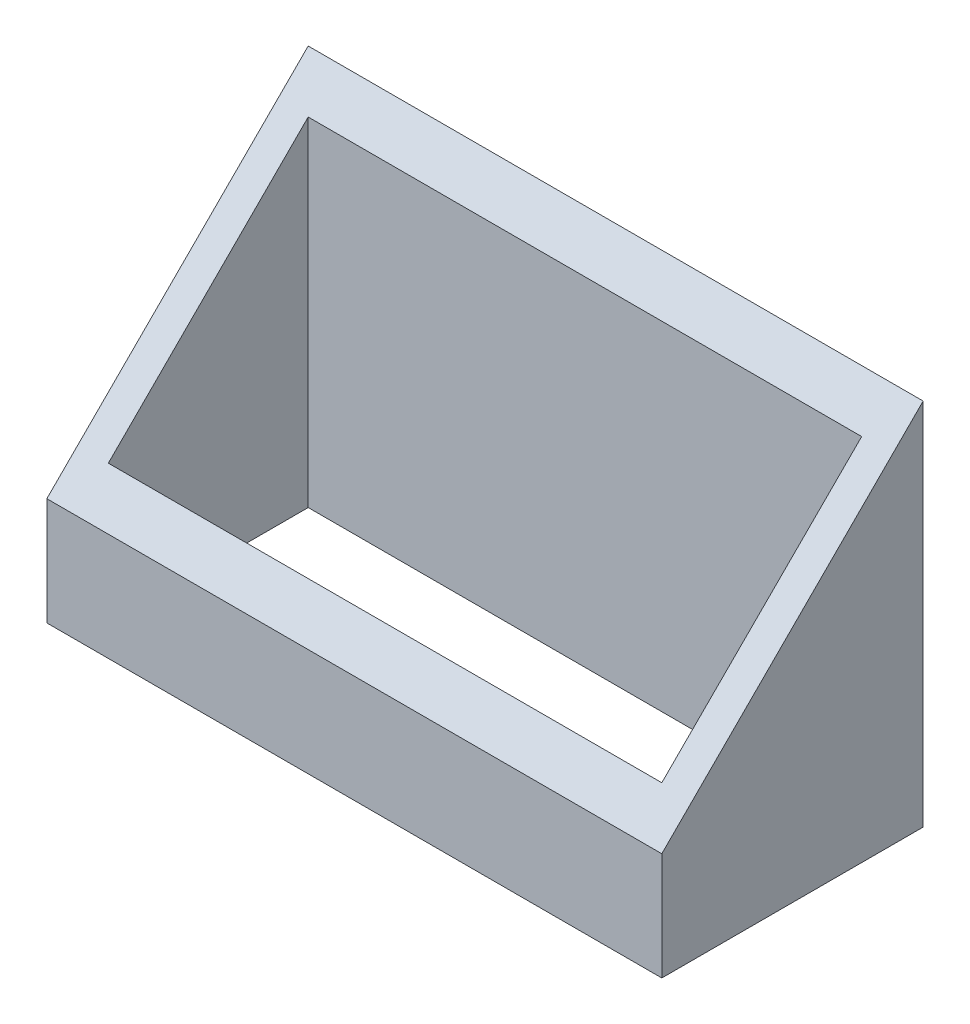
SolidWorks part; units mm, degrees
ref_plane "Front Plane" through (0, 0, 0) normal (0, 0, 1) x (1, 0, 0)
ref_plane "Top Plane" through (0, 0, 0) normal (0, 1, 0) x (1, 0, 0)
ref_plane "Right Plane" through (0, 0, 0) normal (1, 0, 0) x (0, 0, -1)
sketch "Sketch2" plane through (0, 0, 0) normal (1, 0, 0) x (0, 0, -1)
  line L0 (42.5, 60) -> (0, 17.5)
  line L1 (0, 0) -> (42.5, 0)
  line L2 (0, 0) -> (0, 17.5)
  line L4 (42.5, 0) -> (42.5, 60)
  dimension "D1" = 42.5
  dimension "D2" = 60
  dimension "D3" = 45
extrude "Boss-Extrude2" add sketch "Sketch2" along normal blind 100
sketch "Sketch3" plane through (0, 0, 0) normal (0, -1, 0) x (1, 0, 0)
  line L0 (0, 0) -> (0, -42.5) construction
  line L1 (5, -5) -> (95, -5)
  line L2 (5, -5) -> (5, -37.5)
  line L3 (5, -37.5) -> (95, -37.5)
  line L4 (95, -5) -> (95, -37.5)
  line L5 (100, 0) -> (0, 0) construction
  line L6 (100, -42.5) -> (0, -42.5) construction
  line L7 (100, 0) -> (100, -42.5) construction
  dimension "D1" = 5
  dimension "D2" = 5
  dimension "D3" = 5
  dimension "D4" = 5
extrude "Cut-Extrude1" cut sketch "Sketch3" against normal blind 60
